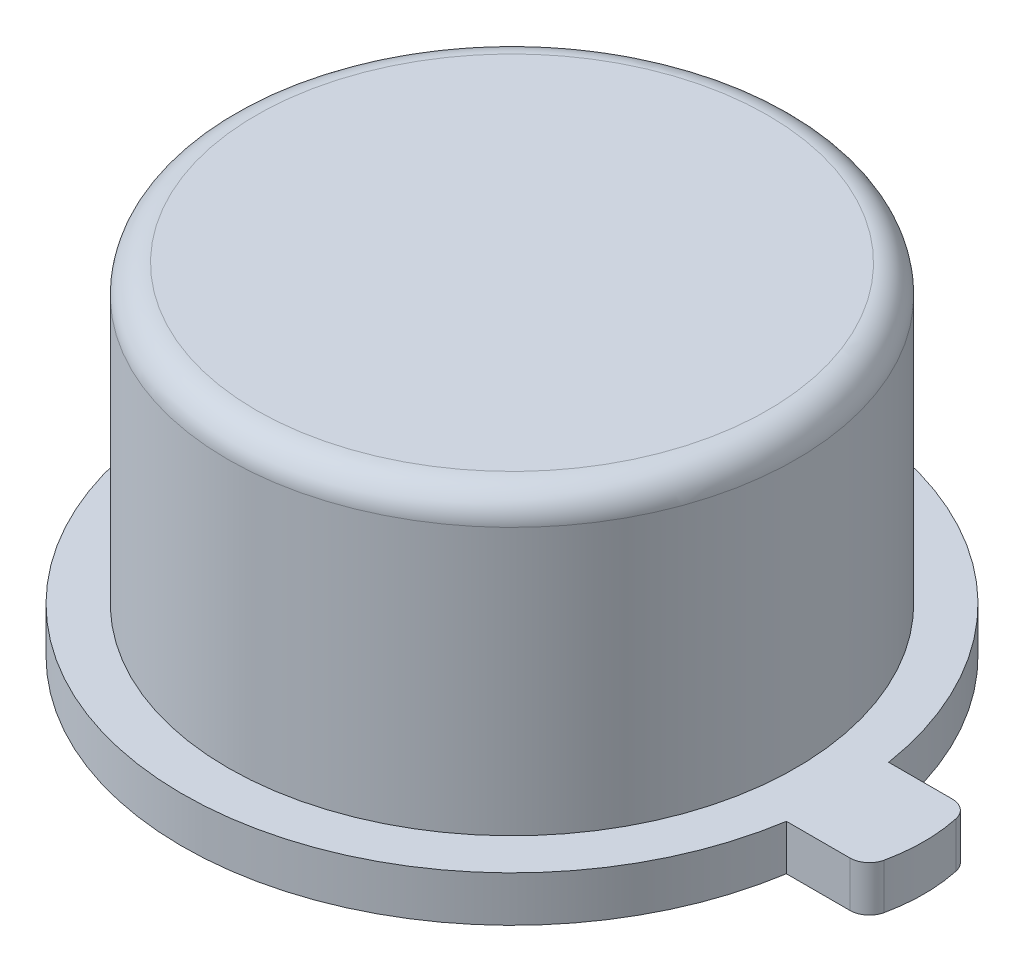
SolidWorks part; units mm, degrees
material "ABS"
ref_plane "Plan de face" through (0, 0, 0) normal (0, 0, 1) x (1, 0, 0)
ref_plane "Plan de dessus" through (0, 0, 0) normal (0, 1, 0) x (1, 0, 0)
ref_plane "Plan de droite" through (0, 0, 0) normal (1, 0, 0) x (0, 0, -1)
sketch "Esquisse1" plane through (0, 0, 0) normal (0, 1, 0) x (1, 0, 0)
  line L1 (5.7297, 0.9) -> (6.85, 0.9)
  line L2 (5.7297, -0.9) -> (6.85, -0.9)
  line L3 (7.1829, 0.6312) -> (7.1829, -0.6312) construction
  arc A0 (5.7297, 0.9) -> (5.7297, -0.9) centre (0, 0) ccw
  circle A1 centre (0, 0) radius 5
  arc A2 (6.85, 0.9) -> (7.1829, 0.6312) centre (6.85, 0.5595) cw
  arc A3 (6.85, -0.9) -> (7.1829, -0.6312) centre (6.85, -0.5595) ccw
  arc A4 (7.1829, 0.6312) -> (7.1829, -0.6312) centre (4.25, 0) cw
  point P4 (5.7297, 0.9)
  point P5 (5.7297, -0.9)
  point P11 (0, 0)
  point P12 (5.8, 0)
  point P17 (7.25, 0)
  point P18 (7.4019, 0.7634)
  dimension "D1" = 11.6
  dimension "D2" = 10
  dimension "D6" = 3
  dimension "D3" = 1.8
  dimension "D4" = 1.45
  dimension "D5" = 0.4
extrude "Support" add sketch "Esquisse1" along normal blind 0.8
sketch "Esquisse2" plane through (0, 0, 0) normal (0, 1, 0) x (1, 0, 0)
  circle A0 centre (0, 0) radius 5
extrude "Bouton" add sketch "Esquisse2" along normal blind 6
fillet "Congé1" radius 0.5 1 edges at (0, 6, 5)
sketch "Esquisse3" plane through (0, 0, 0) normal (0, -1, 0) x (1, 0, 0)
  circle A0 centre (0, 0) radius 3.9
  dimension "D1" = 7.8
extrude "Enlèv. mat.-Extru.1" cut sketch "Esquisse3" against normal blind 5
sketch "Esquisse4" plane through (0, 5, 0) normal (0, -1, 0) x (1, 0, 0)
  line L0 (-0.5, 1.9365) -> (-0.5, 3.8678)
  line L1 (0.5, 1.9365) -> (0.5, 3.8678)
  line L2 (-0.5, 2.9022) -> (0.5, 2.9022) construction
  line L3 (1.9365, 0.5) -> (3.8678, 0.5)
  line L4 (1.9365, -0.5) -> (3.8678, -0.5)
  line L5 (0.5, -1.9365) -> (0.5, -3.8678)
  line L6 (-0.5, -1.9365) -> (-0.5, -3.8678)
  line L7 (-1.9365, -0.5) -> (-3.8678, -0.5)
  line L8 (-1.9365, 0.5) -> (-3.8678, 0.5)
  circle A0 centre (0, 0) radius 0.85
  arc A1 (-0.5, 1.9365) -> (-1.9365, 0.5) centre (0, 0) ccw
  circle A2 centre (0, 0) radius 3.9 construction
  arc A3 (-0.5, 3.8678) -> (0.5, 3.8678) centre (0, 0) cw
  arc A4 (3.8678, 0.5) -> (3.8678, -0.5) centre (0, 0) cw
  arc A5 (0.5, -3.8678) -> (-0.5, -3.8678) centre (0, 0) cw
  arc A6 (-3.8678, -0.5) -> (-3.8678, 0.5) centre (0, 0) cw
  arc A7 (-1.9365, -0.5) -> (-0.5, -1.9365) centre (0, 0) ccw
  arc A8 (1.9365, 0.5) -> (0.5, 1.9365) centre (0, 0) ccw
  arc A9 (0.5, -1.9365) -> (1.9365, -0.5) centre (0, 0) ccw
  point P12 (0, 2.9022)
  point P27 (0, 0)
  dimension "D1" = 1.7
  dimension "D2" = 4
  dimension "D3" = 1
  dimension "D4" = 4
extrude "Dessous" add sketch "Esquisse4" along normal blind 4.4
